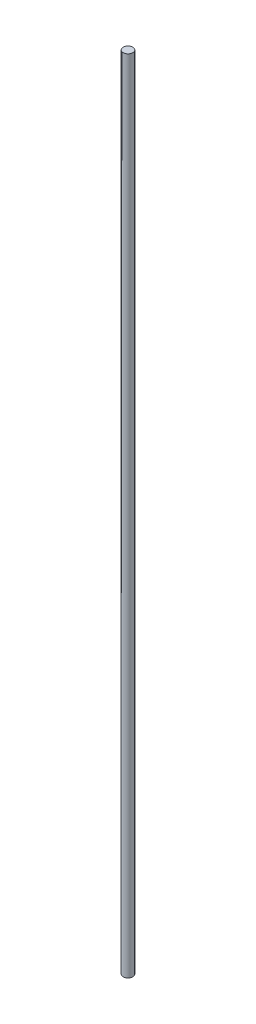
SolidWorks part; units mm, degrees
ref_plane "前视基准面" through (0, 0, 0) normal (0, 0, 1) x (1, 0, 0)
ref_plane "上视基准面" through (0, 0, 0) normal (0, 1, 0) x (1, 0, 0)
ref_plane "右视基准面" through (0, 0, 0) normal (1, 0, 0) x (0, 0, -1)
other "Configuration Table"
sketch "草图1" plane through (0, 0, 0) normal (0, 1, 0) x (1, 0, 0)
  circle A0 centre (-0.7901, -0.1294) radius 1.5
  dimension "D1" = 3
extrude "凸台-拉伸1" add sketch "草图1" along normal blind 250
